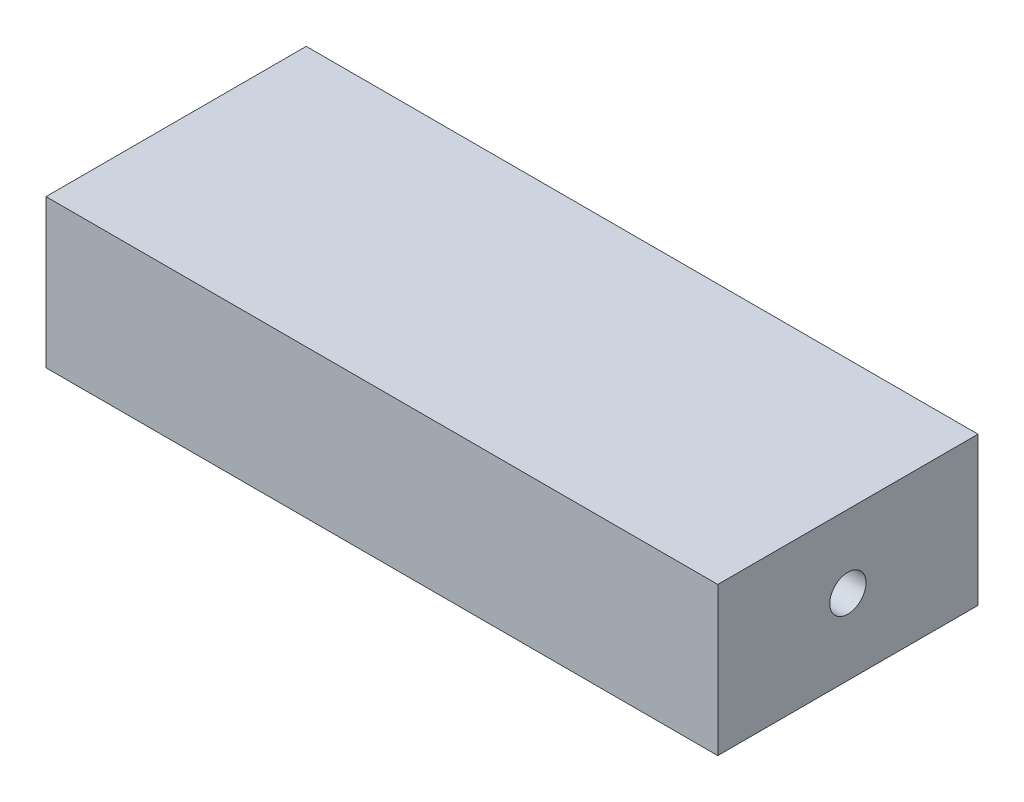
SolidWorks part; units mm, degrees
ref_plane "Front Plane" through (0, 0, 0) normal (0, 0, 1) x (1, 0, 0)
ref_plane "Top Plane" through (0, 0, 0) normal (0, 1, 0) x (1, 0, 0)
ref_plane "Right Plane" through (0, 0, 0) normal (1, 0, 0) x (0, 0, -1)
sketch "Sketch1" plane through (0, 0, 0) normal (0, 1, 0) x (1, 0, 0)
  line L1 (-111, 43) -> (111, 43)
  line L2 (-111, 43) -> (-111, -43)
  line L3 (-111, -43) -> (111, -43)
  line L4 (111, 43) -> (111, -43)
  line L5 (-111, 43) -> (111, -43) construction
  line L6 (-111, -43) -> (111, 43) construction
  point P0 (0, 0)
extrude "Boss-Extrude1" add sketch "Sketch1" along normal blind 22
sketch "Sketch2" plane through (111, 0, 0) normal (1, 0, 0) x (0, 0, -1)
  circle A0 centre (0, 11) radius 6
extrude "Cut-Extrude1" cut sketch "Sketch2" against normal blind 30
sketch "Sketch3" plane through (0, 0, 0) normal (0, -1, 0) x (1, 0, 0)
  line L1 (-111, 43) -> (111, 43)
  line L2 (-111, 43) -> (-111, -43)
  line L3 (-111, -43) -> (111, -43)
  line L4 (111, 43) -> (111, -43)
extrude "Boss-Extrude2" add sketch "Sketch3" along normal blind 14
sketch "Sketch4" plane through (0, 22, 0) normal (0, 1, 0) x (1, 0, 0)
  line L1 (-111, 43) -> (111, 43)
  line L2 (-111, 43) -> (-111, -43)
  line L3 (-111, -43) -> (111, -43)
  line L4 (111, 43) -> (111, -43)
extrude "Boss-Extrude3" add sketch "Sketch4" along normal blind 13
